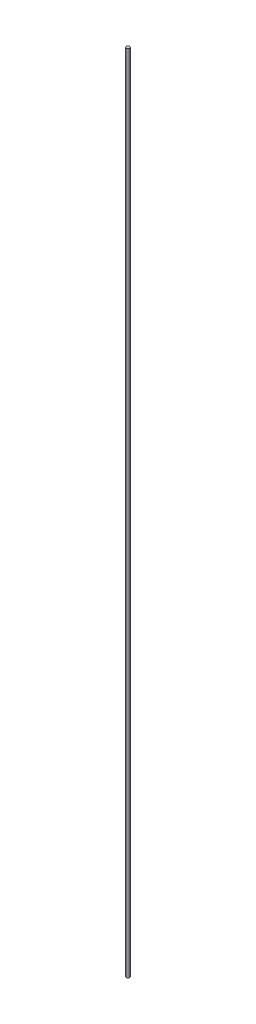
SolidWorks part; units mm, degrees
ref_plane "Front Plane" through (0, 0, 0) normal (0, 0, 1) x (1, 0, 0)
ref_plane "Top Plane" through (0, 0, 0) normal (0, 1, 0) x (1, 0, 0)
ref_plane "Right Plane" through (0, 0, 0) normal (1, 0, 0) x (0, 0, -1)
sketch "Sketch1" plane through (0, 0, 0) normal (0, 1, 0) x (1, 0, 0)
  circle A0 centre (0, 0) radius 1
  dimension "D1" = 2
extrude "Boss-Extrude1" add sketch "Sketch1" along normal blind 493.5
